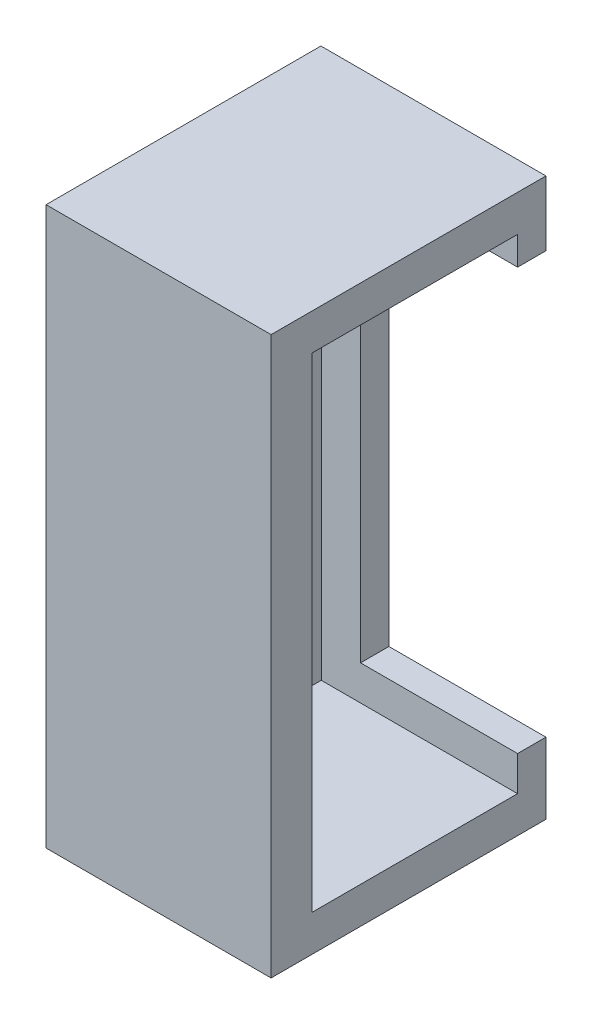
SolidWorks part; units mm, degrees
ref_plane "Спереди" through (0, 0, 0) normal (0, 0, 1) x (1, 0, 0)
ref_plane "Сверху" through (0, 0, 0) normal (0, 1, 0) x (1, 0, 0)
ref_plane "Справа" through (0, 0, 0) normal (1, 0, 0) x (0, 0, -1)
sketch "Эскиз1" plane through (0, 0, 0) normal (0, 0, 1) x (1, 0, 0)
  line L1 (-28.659, 70.9586) -> (28.659, 70.9586)
  line L2 (-28.659, 70.9586) -> (-28.659, -70.9586)
  line L3 (-28.659, -70.9586) -> (28.659, -70.9586)
  line L4 (28.659, 70.9586) -> (28.659, -70.9586)
  line L5 (-28.659, 70.9586) -> (28.659, -70.9586) construction
  line L6 (-28.659, -70.9586) -> (28.659, 70.9586) construction
  point P0 (0, 0)
extrude "Бобышка-Вытянуть1" add sketch "Эскиз1" along normal blind 70
sketch "Эскиз2" plane through (28.659, 0, 0) normal (1, 0, 0) x (0, 0, -1)
  line L1 (-59.5543, 61.6876) -> (-7.2255, 61.6876)
  line L2 (-59.5543, 61.6876) -> (-59.5543, -61.6876)
  line L3 (-59.5543, -61.6876) -> (-7.2255, -61.6876)
  line L4 (-7.2255, 61.6876) -> (-7.2255, -61.6876)
  line L5 (-59.5543, 61.6876) -> (-7.2255, -61.6876) construction
  line L6 (-59.5543, -61.6876) -> (-7.2255, 61.6876) construction
  point P0 (-33.3899, 0)
extrude "Вырез-Вытянуть1" cut sketch "Эскиз2" against normal blind 50
sketch "Эскиз3" plane through (28.659, 0, 0) normal (1, 0, 0) x (0, 0, -1)
  line L0 (-7.2255, -61.6876) -> (-7.2255, 61.6876) construction
  line L1 (-7.2255, 54.442) -> (0, 54.442)
  line L2 (-7.2255, 54.442) -> (-7.2255, -52.8319)
  line L3 (-7.2255, -52.8319) -> (0, -52.8319)
  line L4 (0, 54.442) -> (0, -52.8319)
  line L5 (0, -70.9586) -> (0, 70.9586) construction
extrude "Вырез-Вытянуть2" cut sketch "Эскиз3" against normal blind 40
